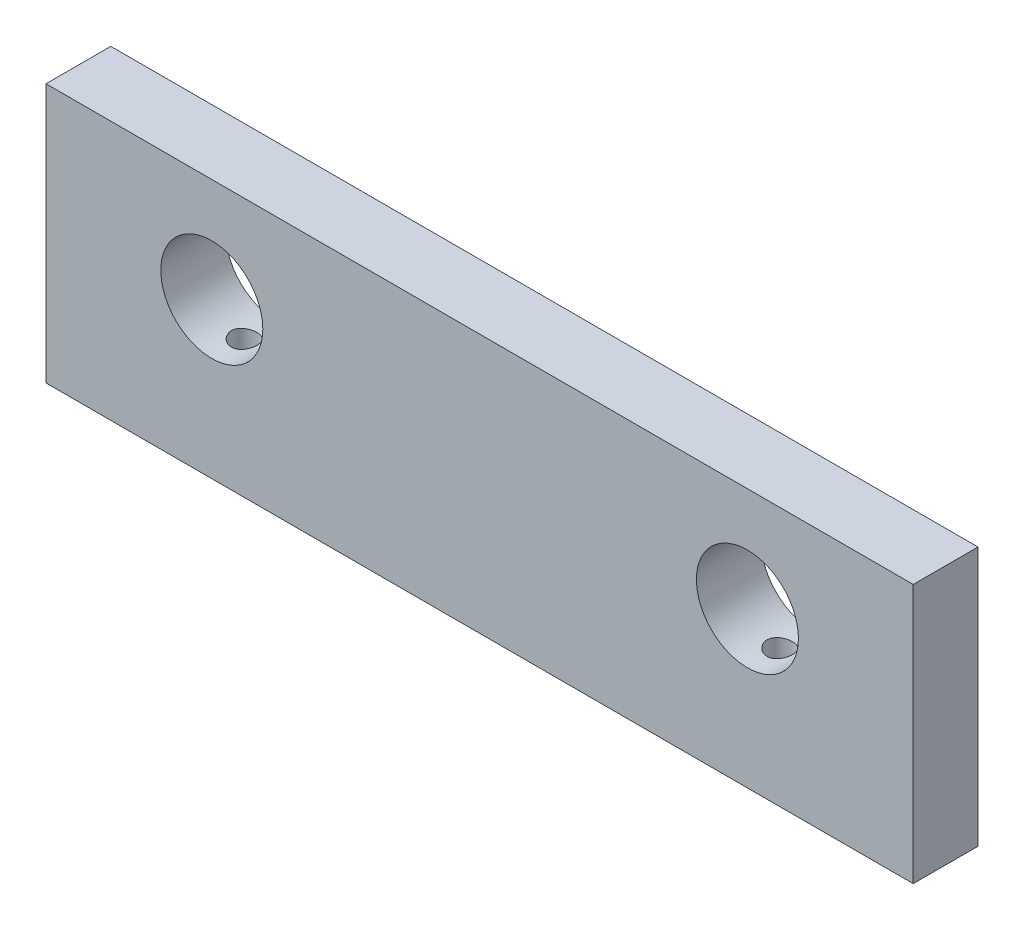
SolidWorks part; units mm, degrees
material "Aleación 1060"
ref_plane "Alzado" through (0, 0, 0) normal (0, 0, 1) x (1, 0, 0)
ref_plane "Planta" through (0, 0, 0) normal (0, 1, 0) x (1, 0, 0)
ref_plane "Vista lateral" through (0, 0, 0) normal (1, 0, 0) x (0, 0, -1)
sketch "Croquis1" plane through (0, 0, 0) normal (0, 0, 1) x (1, 0, 0)
  line L1 (85, -25.4) -> (-85, -25.4)
  line L2 (85, -25.4) -> (85, 25.4)
  line L3 (85, 25.4) -> (-85, 25.4)
  line L4 (-85, -25.4) -> (-85, 25.4)
  line L5 (85, -25.4) -> (-85, 25.4) construction
  line L6 (85, 25.4) -> (-85, -25.4) construction
  circle A0 centre (-52.5, 5) radius 10
  circle A1 centre (52.5, 5) radius 10
  point P0 (0, 0)
  dimension "D3" = 20
  dimension "D4" = 20
  dimension "D1" = 170
  dimension "D2" = 50.8
  dimension "D5" = 105
  dimension "D6" = 52.5
  dimension "D7" = 5
extrude "Saliente-Extruir1" add sketch "Croquis1" along normal blind 12.7 contours L4 L1 L2 L3 A1 A0
sketch "Croquis2" plane through (0, -25.4, 0) normal (0, -1, 0) x (1, 0, 0)
  line L0 (-85, 6.35) -> (85, 6.35) construction
  line L1 (-85, 12.7) -> (-85, 0) construction
  line L2 (85, 12.7) -> (85, 0) construction
  circle A0 centre (-52.5, 6.35) radius 2.5
  circle A1 centre (52.5, 6.35) radius 2.5
  dimension "D1" = 5
  dimension "D2" = 5
  dimension "D3" = 105
  dimension "D4" = 52.5
extrude "Cortar-Extruir1" cut sketch "Croquis2" against normal blind 32.7
sketch "Croquis3" plane through (0, -25.4, 0) normal (0, -1, 0) x (1, 0, 0)
  line L0 (-85, 6.35) -> (85, 6.35) construction
  line L1 (-85, 12.7) -> (-85, 0) construction
  line L2 (85, 12.7) -> (85, 0) construction
  line L3 (0, 0) -> (0, 12.7) construction
  line L4 (85, 12.7) -> (-85, 12.7) construction
  circle A0 centre (-73, 6.35) radius 2.5
  circle A1 centre (73, 6.35) radius 2.5
  dimension "D1" = 5
  dimension "D2" = 12
extrude "Cortar-Extruir2" cut sketch "Croquis3" against normal blind 40
equation "\"D6@Croquis1\"=\"D5@Croquis1\"/2"
equation "\"D4@Croquis2\"=\"D3@Croquis2\"/2"
